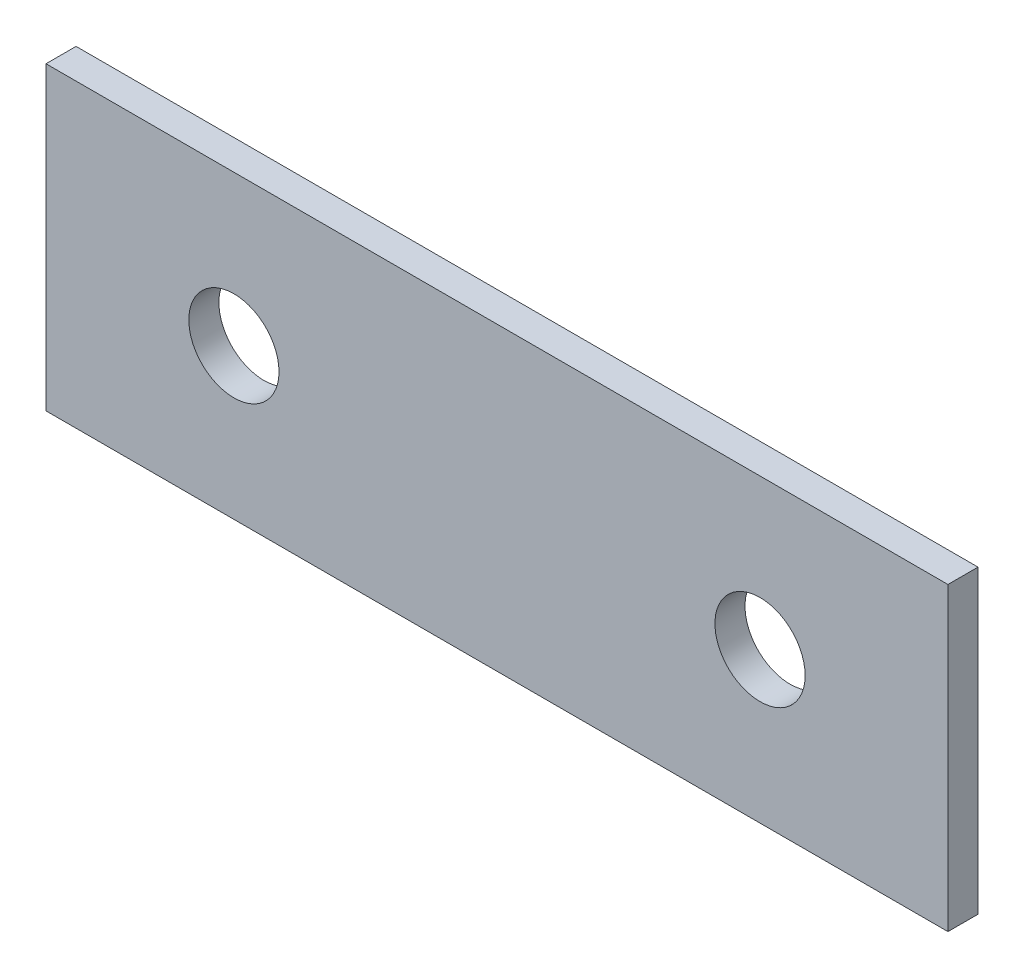
SolidWorks part; units mm, degrees
ref_plane "Plano frontal" through (0, 0, 0) normal (0, 0, 1) x (1, 0, 0)
ref_plane "Plano superior" through (0, 0, 0) normal (0, 1, 0) x (1, 0, 0)
ref_plane "Plano direito" through (0, 0, 0) normal (1, 0, 0) x (0, 0, -1)
sketch "Esboço1" plane through (0, 0, 0) normal (0, 0, 1) x (1, 0, 0)
  line L0 (15, 5) -> (-15, -5) construction
  line L1 (-15, 5) -> (15, 5)
  line L2 (-15, 5) -> (-15, -5)
  line L3 (-15, -5) -> (15, -5)
  line L4 (15, 5) -> (15, -5)
  line L5 (-15, 0) -> (15, 0) construction
  circle A0 centre (-8.75, 0) radius 1.5
  circle A1 centre (8.75, 0) radius 1.5
  dimension "D5" = 3
  dimension "D6" = 3
  dimension "D1" = 10
  dimension "D2" = 30
  dimension "D3" = 6.25
  dimension "D4" = 6.25
extrude "Ressalto-extrusão1" add sketch "Esboço1" along normal blind 1
